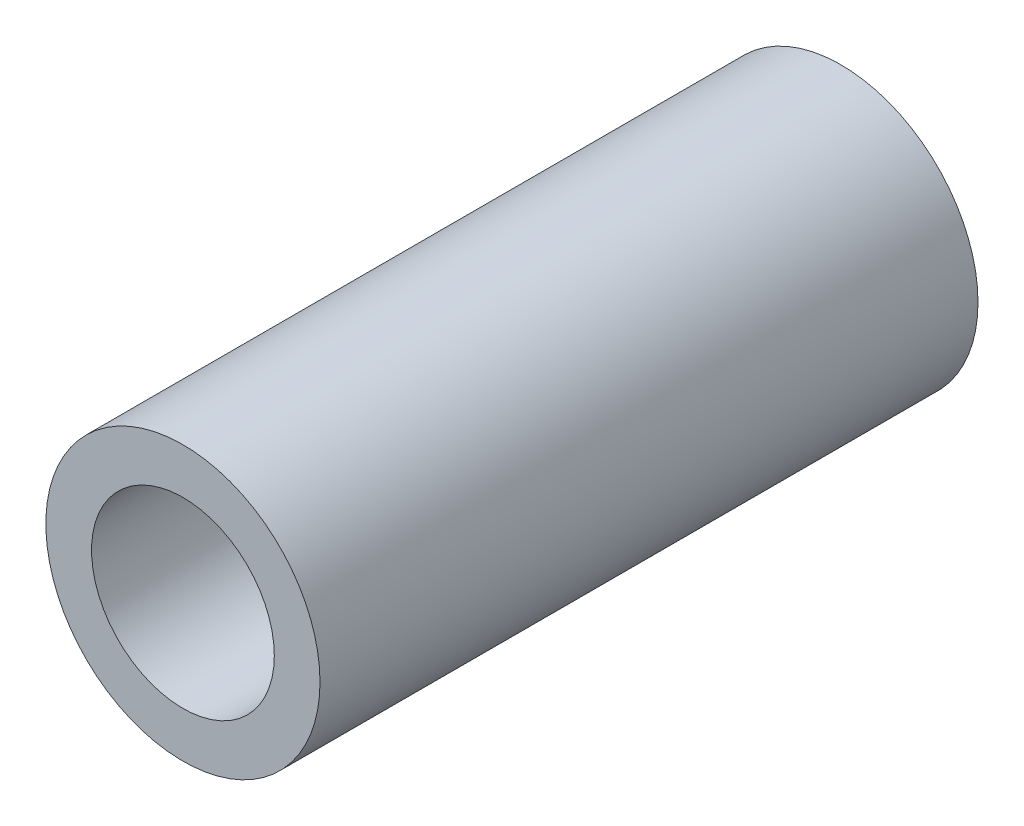
SolidWorks part; units mm, degrees
material "Nylon 101"
ref_plane "Спереди" through (0, 0, 0) normal (0, 0, 1) x (1, 0, 0)
ref_plane "Сверху" through (0, 0, 0) normal (0, 1, 0) x (1, 0, 0)
ref_plane "Справа" through (0, 0, 0) normal (1, 0, 0) x (0, 0, -1)
sketch "Эскиз1" plane through (0, 0, 0) normal (0, 0, 1) x (1, 0, 0)
  circle A4 centre (0, 0) radius 1
  circle A9 centre (0, 0) radius 1.5
  dimension "D1" = 2
  dimension "D2" = 3
extrude "Бобышка-Вытянуть5" add sketch "Эскиз1" along normal blind 7.2 contours A9
